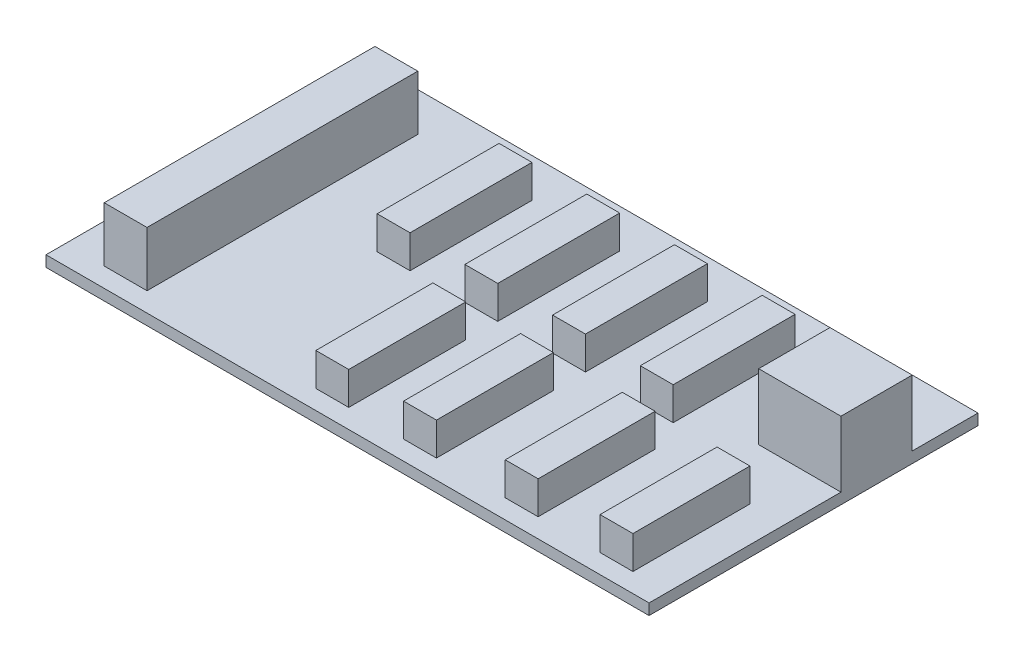
SolidWorks part; units mm, degrees
ref_plane "Front Plane" through (0, 0, 0) normal (0, 0, 1) x (1, 0, 0)
ref_plane "Top Plane" through (0, 0, 0) normal (0, 1, 0) x (1, 0, 0)
ref_plane "Right Plane" through (0, 0, 0) normal (1, 0, 0) x (0, 0, -1)
sketch "Sketch1" plane through (0, 0, 0) normal (0, 1, 0) x (1, 0, 0)
  line L1 (-51.97, -19.8185) -> (58.03, -19.8185)
  line L2 (-51.97, -19.8185) -> (-51.97, 40.1815)
  line L3 (-51.97, 40.1815) -> (58.03, 40.1815)
  line L4 (58.03, -19.8185) -> (58.03, 40.1815)
  dimension "D1" = 110
  dimension "D2" = 60
extrude "Boss-Extrude1" add sketch "Sketch1" along normal blind 2
sketch "Sketch2" plane through (0, 2, 0) normal (0, 1, 0) x (1, 0, 0)
  line L0 (58.03, -19.8185) -> (58.03, 40.1815) construction
  line L1 (58.03, 28.1815) -> (43.03, 28.1815)
  line L2 (58.03, 28.1815) -> (58.03, 15.1815)
  line L3 (58.03, 15.1815) -> (43.03, 15.1815)
  line L4 (43.03, 28.1815) -> (43.03, 15.1815)
  line L5 (58.03, 40.1815) -> (-51.97, 40.1815) construction
  dimension "D1" = 15
  dimension "D2" = 12
  dimension "D3" = 13
extrude "Boss-Extrude2" add sketch "Sketch2" along normal blind 12
sketch "Sketch3" plane through (0, 2, 0) normal (0, 1, 0) x (1, 0, 0)
  line L1 (31.7578, 33.095) -> (25.7578, 33.095)
  line L2 (31.7578, 33.095) -> (31.7578, 10.8555)
  line L3 (31.7578, 10.8555) -> (25.7578, 10.8555)
  line L4 (25.7578, 33.095) -> (25.7578, 10.8555)
  line L5 (15.7578, 33.095) -> (9.7578, 33.095)
  line L6 (15.7578, 33.095) -> (15.7578, 10.8555)
  line L7 (15.7578, 10.8555) -> (9.7578, 10.8555)
  line L8 (9.7578, 33.095) -> (9.7578, 10.8555)
  line L9 (-0.2422, 33.095) -> (-6.2422, 33.095)
  line L10 (-0.2422, 33.095) -> (-0.2422, 10.8555)
  line L11 (-0.2422, 10.8555) -> (-6.2422, 10.8555)
  line L12 (-6.2422, 33.095) -> (-6.2422, 10.8555)
  line L13 (-16.2422, 33.095) -> (-22.2422, 33.095)
  line L14 (-16.2422, 33.095) -> (-16.2422, 10.8555)
  line L15 (-16.2422, 10.8555) -> (-22.2422, 10.8555)
  line L16 (-22.2422, 33.095) -> (-22.2422, 10.8555)
  line L17 (51.5996, 5.0148) -> (45.5996, 5.0148)
  line L18 (51.5996, 5.0148) -> (51.5996, -16.3262)
  line L19 (51.5996, -16.3262) -> (45.5996, -16.3262)
  line L20 (45.5996, 5.0148) -> (45.5996, -16.3262)
  line L21 (34.3022, 5.0148) -> (28.3022, 5.0148)
  line L22 (34.3022, 5.0148) -> (34.3022, -16.3262)
  line L23 (34.3022, -16.3262) -> (28.3022, -16.3262)
  line L24 (28.3022, 5.0148) -> (28.3022, -16.3262)
  line L25 (15.7578, 5.0148) -> (9.7578, 5.0148)
  line L26 (15.7578, 5.0148) -> (15.7578, -16.3262)
  line L27 (15.7578, -16.3262) -> (9.7578, -16.3262)
  line L28 (9.7578, 5.0148) -> (9.7578, -16.3262)
  line L29 (-0.2422, 5.0148) -> (-6.2422, 5.0148)
  line L30 (-0.2422, 5.0148) -> (-0.2422, -16.3262)
  line L31 (-0.2422, -16.3262) -> (-6.2422, -16.3262)
  line L32 (-6.2422, 5.0148) -> (-6.2422, -16.3262)
  dimension "D1" = 6
  dimension "D2" = 6
  dimension "D3" = 6
  dimension "D4" = 6
  dimension "D5" = 10
  dimension "D6" = 10
  dimension "D7" = 10
  dimension "D8" = 6
extrude "Boss-Extrude3" add sketch "Sketch3" along normal blind 6
sketch "Sketch4" plane through (0, 2, 0) normal (0, 1, 0) x (1, 0, 0)
  line L1 (-37.0686, 33.095) -> (-44.88, 33.095)
  line L2 (-37.0686, 33.095) -> (-37.0686, -16.2905)
  line L3 (-37.0686, -16.2905) -> (-44.88, -16.2905)
  line L4 (-44.88, 33.095) -> (-44.88, -16.2905)
extrude "Boss-Extrude4" add sketch "Sketch4" along normal blind 10
